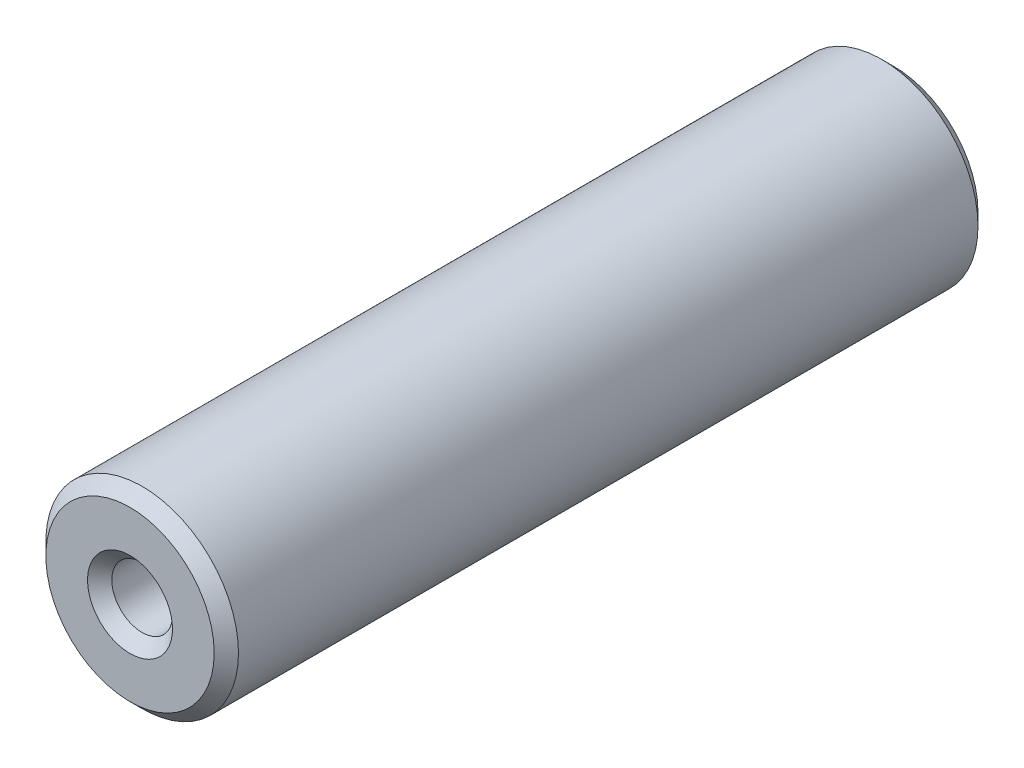
SolidWorks part; units mm, degrees
ref_plane "Front Plane" through (0, 0, 0) normal (0, 0, 1) x (1, 0, 0)
ref_plane "Top Plane" through (0, 0, 0) normal (0, 1, 0) x (1, 0, 0)
ref_plane "Right Plane" through (0, 0, 0) normal (1, 0, 0) x (0, 0, -1)
sketch "Sketch1" plane through (0, 0, 0) normal (0, 0, 1) x (1, 0, 0)
  circle A0 centre (0, 0) radius 3.9688
  dimension "D1" = 7.9375
extrude "Boss-Extrude1" add sketch "Sketch1" along normal blind 31.475
sketch "Sketch3" plane through (0, 0, 31.475) normal (0, 0, 1) x (1, 0, 0)
  circle A0 centre (0, 0) radius 1.25
  dimension "D1" = 2.5
extrude "Cut-Extrude1" cut sketch "Sketch3" against normal blind 4.5
sketch "Sketch4" plane through (0, 0, 0) normal (0, 0, -1) x (-1, 0, 0)
  circle A0 centre (0, 0) radius 1.3521
extrude "Cut-Extrude2" cut sketch "Sketch4" against normal blind 4.5
chamfer "Chamfer1" distance 0.5 angle 45 4 edges at (-1.3521, 0, 0) (3.9688, 0, 0) (3.9688, 0, 31.475) (1.25, 0, 31.475)
